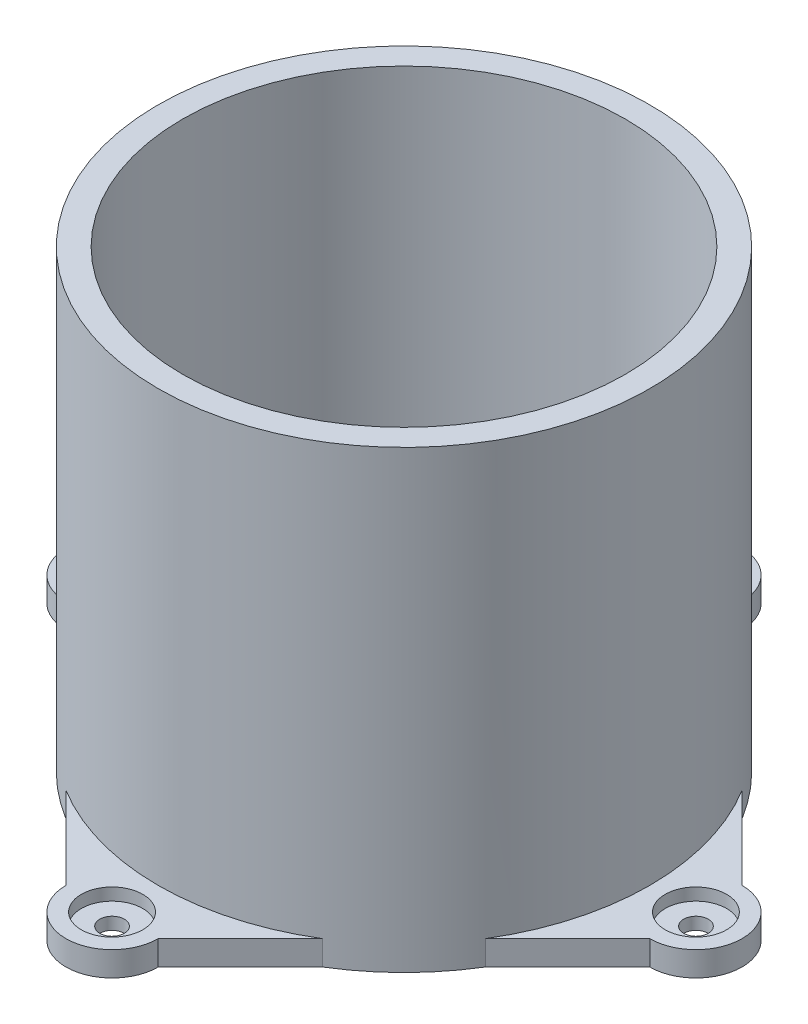
SolidWorks part; units mm, degrees
ref_plane "Front Plane" through (0, 0, 0) normal (0, 0, 1) x (1, 0, 0)
ref_plane "Top Plane" through (0, 0, 0) normal (0, 1, 0) x (1, 0, 0)
ref_plane "Right Plane" through (0, 0, 0) normal (1, 0, 0) x (0, 0, -1)
sketch "Sketch1" plane through (0, 0, 0) normal (0, 1, 0) x (1, 0, 0)
  line L0 (0, 40) -> (0, -40) construction
  line L1 (-40, 0) -> (40, 0) construction
  line L2 (-40, 0) -> (-59.2804, 0) construction
  line L3 (0, 0) -> (-67.7307, 67.7307) construction
  line L4 (0, 0) -> (54.002, -54.002) construction
  line L5 (0, 0) -> (61.2859, 61.2859) construction
  line L6 (61.2859, 61.2859) -> (-53.2598, -53.2598) construction
  line L7 (-47.5, 7.5) -> (-34.1144, 20.8856)
  line L9 (7.5, 47.5) -> (20.8856, 34.1144)
  line L11 (47.5, -7.5) -> (34.1144, -20.8856)
  line L13 (-7.5, -47.5) -> (-20.8856, -34.1144)
  line L14 (-20.8856, 34.1144) -> (-7.5, 47.5)
  line L15 (34.1144, 20.8856) -> (47.5, 7.5)
  line L16 (-34.1144, -20.8856) -> (-47.5, -7.5)
  line L17 (20.8856, -34.1144) -> (7.5, -47.5)
  arc A0 (-34.1144, -20.8856) -> (-20.8856, -34.1144) centre (0, 0) ccw
  arc A1 (-47.5, 7.5) -> (-47.5, -7.5) centre (-47.5, 0) ccw
  arc A2 (7.5, 47.5) -> (-7.5, 47.5) centre (0, 47.5) ccw
  arc A3 (47.5, -7.5) -> (47.5, 7.5) centre (47.5, 0) ccw
  arc A4 (-7.5, -47.5) -> (7.5, -47.5) centre (0, -47.5) ccw
  arc A5 (-20.8856, 34.1144) -> (-34.1144, 20.8856) centre (0, 0) ccw
  arc A6 (34.1144, 20.8856) -> (20.8856, 34.1144) centre (0, 0) ccw
  arc A7 (20.8856, -34.1144) -> (34.1144, -20.8856) centre (0, 0) ccw
  point P19 (0, 0)
  dimension "D1" = 80
  dimension "D2" = 15
  dimension "D4" = 45
  dimension "D5" = 45
  dimension "D3" = 4
extrude "Boss-Extrude1" add sketch "Sketch1" along normal blind 4
sketch "Sketch2" plane through (0, 4, 0) normal (0, 1, 0) x (1, 0, 0)
  circle A0 centre (0, 0) radius 40 construction
  circle A1 centre (-47.5, 0) radius 2
  circle A2 centre (0, 47.5) radius 2
  circle A3 centre (47.5, 0) radius 2
  circle A4 centre (0, -47.5) radius 2
  point P15 (0, 0)
  dimension "D2" = 4
  dimension "D1" = 4
extrude "Cut-Extrude1" cut sketch "Sketch2" against normal blind 4
sketch "Sketch3" plane through (0, 4, 0) normal (0, 1, 0) x (1, 0, 0)
  circle A0 centre (0, 0) radius 40 construction
  circle A1 centre (-47.5, 0) radius 5
  circle A2 centre (-47.5, 0) radius 2 construction
  circle A3 centre (0, 47.5) radius 5
  circle A4 centre (47.5, 0) radius 5
  circle A5 centre (0, -47.5) radius 5
  point P17 (0, 0)
  dimension "D1" = 3
  dimension "D2" = 4
extrude "Cut-Extrude2" cut sketch "Sketch3" against normal blind 2
sketch "Sketch4" plane through (0, 4, 0) normal (0, 1, 0) x (1, 0, 0)
  circle A0 centre (0, 0) radius 40
  circle A1 centre (0, 0) radius 36
  dimension "D1" = 80
  dimension "D2" = 4
extrude "Boss-Extrude2" add sketch "Sketch4" along normal blind 70
